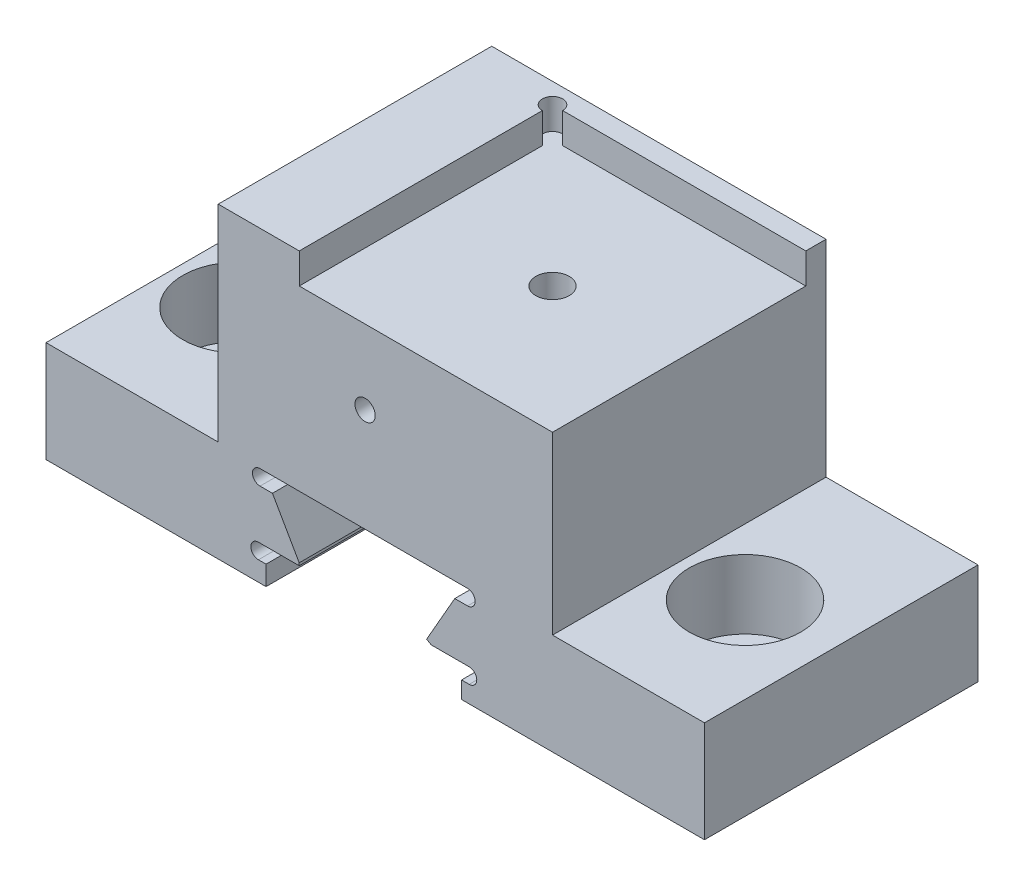
SolidWorks part; units mm, degrees
material "6061 合金"
ref_plane "前视基准面" through (0, 0, 0) normal (0, 0, 1) x (1, 0, 0)
ref_plane "上视基准面" through (0, 0, 0) normal (0, 1, 0) x (1, 0, 0)
ref_plane "右视基准面" through (0, 0, 0) normal (1, 0, 0) x (0, 0, -1)
sketch "草图1" plane through (0, 0, 0) normal (0, 1, 0) x (1, 0, 0)
  line L1 (-14.5, 14.5) -> (14.5, 14.5)
  line L2 (-14.5, 14.5) -> (-14.5, -14.5)
  line L3 (-14.5, -14.5) -> (14.5, -14.5)
  line L4 (14.5, 14.5) -> (14.5, -14.5)
  line L5 (-14.5, 14.5) -> (14.5, -14.5) construction
  line L6 (-14.5, -14.5) -> (14.5, 14.5) construction
  point P0 (0, 0)
  dimension "D1" = 29
  dimension "D2" = 29
extrude "凸台-拉伸1" add sketch "草图1" along normal blind 5
sketch "草图2" plane through (0, 5, 0) normal (0, -1, 0) x (1, 0, 0)
  line L1 (-12.5, 12.5) -> (12.5, 12.5)
  line L2 (-12.5, 12.5) -> (-12.5, -12.5)
  line L3 (-12.5, -12.5) -> (12.5, -12.5)
  line L4 (12.5, 12.5) -> (12.5, -12.5)
  line L5 (-12.5, 12.5) -> (12.5, -12.5) construction
  line L6 (-12.5, -12.5) -> (12.5, 12.5) construction
  point P0 (0, 0)
  dimension "D1" = 25
  dimension "D2" = 25
extrude "切除-拉伸1" cut sketch "草图2" along normal blind 3
sketch "草图3" plane through (0, 0, 0) normal (0, -1, 0) x (-1, 0, 0)
  line L1 (-14.5, -14.5) -> (20.5, -14.5)
  line L2 (-14.5, -14.5) -> (-14.5, 14.5)
  line L3 (-14.5, 14.5) -> (20.5, 14.5)
  line L4 (20.5, -14.5) -> (20.5, 14.5)
  dimension "D1" = 29
  dimension "D2" = 35
extrude "拉到底部滑块" add sketch "草图3" along normal up to surface (25.3412 mm away)
sketch "草图5" plane through (0, 2, 0) normal (0, 1, 0) x (1, 0, 0)
  circle A0 centre (0, 0) radius 2.1526
hole_wizard "M4 螺纹孔1" positions "3D草图1" profile "草图6" tap size "M4" standard "GB"
sketch3d "3D草图1"
  point P0 (0, 2, 0)
sketch "草图6" plane through (0, 2, 0) normal (1, 0, 0) x (0, 0, 1)
  line L0 (0, 0) -> (0, 11.0914)
  line L1 (0, 11.0914) -> (1.65, 10.1)
  line L2 (1.65, 10.1) -> (1.65, 0)
  line L5 (1.65, 0) -> (0, 0)
  line L10 (0, 11.0914) -> (-1.65, 10.1) construction
  line L11 (0, -6.35) -> (0, 107.95) construction
  dimension "螺纹孔钻头直径" = 3.3
  dimension "螺纹孔钻头深度" = 10.1
  dimension "导头角度" = 118
cosmetic thread "孔螺蚊线1" parameters "D1"=8, "D2"=4
sketch "草图9" plane through (0, 5, 0) normal (0, 1, 0) x (1, 0, 0)
  circle A0 centre (-12.5, 12.5) radius 1
extrude "切除-拉伸2" cut sketch "草图9" against normal up to surface (3 mm away) up to face at (0, 2, 1.65)
sketch "草图11" plane through (-14.5, 0, 0) normal (-1, 0, 0) x (0, 0, 1)
  line L4 (-14.5, 0) -> (14.5, 0)
  line L5 (14.5, 0) -> (14.5, 5)
  line L6 (14.5, 5) -> (-14.5, 5)
  line L7 (-14.5, 5) -> (-14.5, 0)
  line L8 (-14.5, 0) -> (14.5, 0)
  line L9 (14.5, 0) -> (14.5, 5)
  line L10 (14.5, 5) -> (-14.5, 5)
  line L11 (-14.5, 5) -> (-14.5, 0)
  dimension "D1" = 0
extrude "凸台-拉伸4" add sketch "草图11" along normal up to surface (6 mm away) up to face at (-20.5, -12.6706, 0)
sketch "草图17" plane through (0, 5, 0) normal (0, 1, 0) x (1, 0, 0)
  line L0 (-20.5, -14.5) -> (14.5, -14.5) construction
  line L1 (14.5, -14.5) -> (14.5, 14.5) construction
  line L2 (-20.5, -14.5) -> (14.5, -14.5)
  line L3 (14.5, -14.5) -> (14.5, 14.5)
  line L4 (-20.5, -12.5) -> (12.5, -12.5)
  line L5 (12.5, -12.5) -> (12.5, 14.5)
  line L6 (12.5, 14.5) -> (14.5, 14.5)
  line L7 (-20.5, -12.5) -> (-20.5, -14.5)
  dimension "D1" = 2
extrude "切除-拉伸8" cut sketch "草图17" against normal through all
sketch "草图18" plane through (0, -25.3412, 0) normal (0, -1, 0) x (1, 0, 0)
  line L0 (0, 0) -> (-6, 0) construction
  line L1 (16.5, 0) -> (-16.5, 0) construction
  line L2 (-6, 0) -> (-6, 12.5) construction
  line L3 (12.5, 12.5) -> (-20.5, 12.5) construction
  circle A0 centre (-6, 0) radius 1.512
  dimension "D1" = 6
sketch "草图19" plane through (0, -25.3412, 0) normal (0, -1, 0) x (-1, 0, 0)
  line L0 (-12.5, -12.5) -> (20.5, -12.5) construction
  line L1 (46, -12.5) -> (-34, -12.5)
  line L2 (46, -12.5) -> (46, 12.5)
  line L3 (46, 12.5) -> (-34, 12.5)
  line L4 (-34, -12.5) -> (-34, 12.5)
  line L5 (46, -12.5) -> (-34, 12.5) construction
  line L6 (46, 12.5) -> (-34, -12.5) construction
  point P0 (6, 0)
  dimension "D1" = 80
extrude "凸台-拉伸5" add sketch "草图19" against normal blind 10
sketch "草图21" plane through (0, -15.3412, 0) normal (0, 1, 0) x (1, 0, 0)
  line L0 (-6, 0) -> (-31, 0)
  line L3 (-16.5, 0) -> (16.5, 0) construction
  line L4 (-6, 0) -> (19, 0)
  dimension "D1" = 25
  dimension "D2" = 25
hole_wizard "打孔尺寸(%根据)内六角圆柱头螺钉的类型1" positions "3D草图2" profile "草图22" counterbore size "M6" standard "GB"
sketch3d "3D草图2"
  point P0 (-31, -15.3412, 0)
  point P3 (19, -15.3412, 0)
sketch "草图22" plane through (-31, -15.3412, 0) normal (1, 0, 0) x (0, 0, 1)
  line L0 (0, 0) -> (0, 12.0828)
  line L1 (0, 12.0828) -> (3.3, 10.1)
  line L2 (3.3, 10.1) -> (3.3, 6.8)
  line L3 (3.3, 6.8) -> (5.5, 6.8)
  line L4 (5.5, 6.8) -> (5.5, 0)
  line L5 (5.5, 0) -> (0, 0)
  line L10 (0, 12.0828) -> (-3.3, 10.1) construction
  line L11 (0, -6.35) -> (0, 107.95) construction
  dimension "孔直径" = 6.6
  dimension "孔深度" = 10.1
  dimension "柱形沉头孔直径" = 11
  dimension "柱形沉头孔深度" = 6.8
  dimension "导头角度" = 118
sketch "草图23" plane through (0, 0, -12.5) normal (0, 0, -1) x (-1, 0, 0)
  line L1 (-34, -15.3412) -> (46, -15.3412)
  line L2 (-34, -15.3412) -> (-34, -25.3412)
  line L3 (-34, -25.3412) -> (46, -25.3412)
  line L4 (46, -15.3412) -> (46, -25.3412)
extrude "凸台-拉伸6" add sketch "草图23" along normal up to surface (2 mm away) up to face at (-4, -10.1706, -14.5)
sketch "草图24" plane through (-46, 0, 0) normal (-1, 0, 0) x (0, 0, 1)
  line L4 (-14.5, -25.3412) -> (12.5, -25.3412)
  line L5 (12.5, -25.3412) -> (12.5, -15.3412)
  line L6 (12.5, -15.3412) -> (-14.5, -15.3412)
  line L7 (-14.5, -15.3412) -> (-14.5, -25.3412)
  line L8 (-14.5, -25.3412) -> (12.5, -25.3412)
  line L9 (12.5, -25.3412) -> (12.5, -15.3412)
  line L10 (12.5, -15.3412) -> (-14.5, -15.3412)
  line L11 (-14.5, -15.3412) -> (-14.5, -25.3412)
  dimension "D1" = 0
extrude "切除-拉伸9" cut sketch "草图24" against normal blind 2
sketch "草图25" plane through (0, -25.3412, 0) normal (0, -1, 0) x (1, 0, 0)
  line L0 (-31, 0) -> (-21, 0) construction
  line L1 (-6, 0) -> (-31, 0) construction
  line L2 (19, 0) -> (9, 0) construction
  line L3 (-6, 0) -> (19, 0) construction
  dimension "D1" = 10
hole_wizard "大小mm 暗销孔1" positions "3D草图3" profile "草图26" hole size "Ø4.0" standard "GB"
sketch3d "3D草图3"
  point P0 (-21, -25.3412, 0)
sketch "草图26" plane through (-21, -25.3412, 0) normal (1, 0, 0) x (0, 0, -1)
  line L0 (0, 0) -> (0, 6.2017)
  line L1 (0, 6.2017) -> (2, 5)
  line L2 (2, 5) -> (2, 0)
  line L5 (2, 0) -> (0, 0)
  line L10 (0, 6.2017) -> (-2, 5) construction
  line L11 (0, -6.35) -> (0, 107.95) construction
  dimension "孔直径" = 4
  dimension "孔深度" = 5
  dimension "导头角度" = 118
sketch "草图27" plane through (0, -25.3412, 0) normal (0, -1, 0) x (1, 0, 0)
  line L0 (8.5, 0) -> (9.5, 0) construction
  line L1 (8.5, 2) -> (9.5, 2)
  line L2 (8.5, -2) -> (9.5, -2)
  arc A0 (8.5, 2) -> (8.5, -2) centre (8.5, 0) ccw
  arc A1 (9.5, -2) -> (9.5, 2) centre (9.5, 0) ccw
  circle A2 centre (-21, 0) radius 2 construction
  point P2 (9, 0)
  dimension "D1" = 1
extrude "切除-拉伸10" cut sketch "草图27" against normal blind 5
sketch "草图28" plane through (0, 0, 12.5) normal (0, 0, 1) x (1, 0, 0)
  line L0 (-6, -25.3412) -> (-6, -5.3412) construction
  circle A0 centre (-6, -5.3412) radius 1
  dimension "D1" = 20
extrude "切除-拉伸11" cut sketch "草图28" against normal blind 2
hole_wizard "M6 螺纹孔1" positions "3D草图4" profile "草图29" tap size "M6" standard "GB"
sketch3d "3D草图4"
  point P0 (-6, -25.3412, 0)
sketch "草图29" plane through (-6, -25.3412, 0) normal (1, 0, 0) x (0, 0, -1)
  line L0 (0, 0) -> (0, 11.5022)
  line L1 (0, 11.5022) -> (2.5, 10)
  line L2 (2.5, 10) -> (2.5, 0)
  line L5 (2.5, 0) -> (0, 0)
  line L10 (0, 11.5022) -> (-2.5, 10) construction
  line L11 (0, -6.35) -> (0, 107.95) construction
  dimension "螺纹孔钻头直径" = 5
  dimension "螺纹孔钻头深度" = 10
  dimension "导头角度" = 118
cosmetic thread "孔螺蚊线2" parameters "D1"=10, "D2"=6
sketch "草图30" plane through (0, -25.3412, 0) normal (0, -1, 0) x (-1, 0, 0)
  circle A0 centre (21, 0) radius 2
  circle A1 centre (-9, 0) radius 2
extrude "切除-拉伸12" cut sketch "草图31" against normal through all and the other way through all
sketch "草图31" plane through (-6.0032, 14.6588, 10.4718) normal (0, 0, 1) x (1, 0, 0)
  line L13 (10.1171, -31.7) -> (8.8541, -31.7)
  line L14 (8.8541, -31.7) -> (6.0752, -36.5641)
  line L15 (6.0752, -36.5641) -> (6.5318, -36.825)
  line L16 (6.5318, -36.825) -> (10.275, -36.825)
  line L17 (10.275, -38.325) -> (9.525, -38.325)
  line L18 (9.525, -38.325) -> (9.525, -40)
  line L19 (-9.7761, -40) -> (-9.7761, -38.0744)
  line L20 (-9.7761, -38.0744) -> (-10.5261, -38.0744)
  line L21 (-10.5261, -36.5744) -> (-6.5013, -36.5744)
  line L22 (-6.5013, -36.5744) -> (-6.5013, -36.3244)
  line L23 (-6.5013, -36.3244) -> (-9.1432, -31.7)
  line L24 (-9.1432, -31.7) -> (-10.3692, -31.7)
  line L25 (-10.3692, -30.2) -> (10.1171, -30.2)
  line L26 (-9.7761, -40) -> (9.525, -40)
  arc A4 (10.1171, -31.7) -> (10.1171, -30.2) centre (10.1171, -30.95) ccw
  arc A5 (10.275, -38.325) -> (10.275, -36.825) centre (10.275, -37.575) ccw
  arc A6 (-10.5261, -36.5744) -> (-10.5261, -38.0744) centre (-10.5261, -37.3244) ccw
  arc A7 (-10.3692, -30.2) -> (-10.3692, -31.7) centre (-10.3692, -30.95) ccw
sketch "草图32" plane through (-44, 0, 0) normal (-1, 0, 0) x (0, 0, 1)
  line L4 (-14.5, -15.3412) -> (-14.5, -25.3412)
  line L5 (-14.5, -25.3412) -> (12.5, -25.3412)
  line L6 (12.5, -25.3412) -> (12.5, -15.3412)
  line L7 (12.5, -15.3412) -> (-14.5, -15.3412)
  line L8 (-14.5, -15.3412) -> (-14.5, -25.3412)
  line L9 (-14.5, -25.3412) -> (12.5, -25.3412)
  line L10 (12.5, -25.3412) -> (12.5, -15.3412)
  line L11 (12.5, -15.3412) -> (-14.5, -15.3412)
  dimension "D1" = 0
extrude "切除-拉伸13" cut sketch "草图32" against normal blind 6.5
sketch "草图33" plane through (34, 0, 0) normal (1, 0, 0) x (0, 0, -1)
  line L4 (-12.5, -25.3412) -> (14.5, -25.3412)
  line L5 (14.5, -25.3412) -> (14.5, -15.3412)
  line L6 (14.5, -15.3412) -> (-12.5, -15.3412)
  line L7 (-12.5, -15.3412) -> (-12.5, -25.3412)
  line L8 (-12.5, -25.3412) -> (14.5, -25.3412)
  line L9 (14.5, -25.3412) -> (14.5, -15.3412)
  line L10 (14.5, -15.3412) -> (-12.5, -15.3412)
  line L11 (-12.5, -15.3412) -> (-12.5, -25.3412)
  dimension "D1" = 0
extrude "切除-拉伸14" cut sketch "草图33" against normal blind 6.5
sketch "草图34" plane through (0, -25.3412, 0) normal (0, -1, 0) x (1, 0, 0)
  line L0 (-21, 0) -> (-21, -8) construction
  line L2 (9, -8) -> (9, 0) construction
  line L4 (-21, 0) -> (-21, 8) construction
  circle A0 centre (-21, -8) radius 2
  circle A1 centre (9, -8) radius 2
  circle A2 centre (-21, 8) radius 2
  point P9 (9, -4.1683)
  point P10 (9, -6.1891)
sketch "草图35" plane through (0, -25.3412, 0) normal (0, -1, 0) x (1, 0, 0)
  line L0 (8.5, -8) -> (9.5, -8) construction
  line L2 (8.5, -6) -> (9.5, -6)
  line L3 (8.5, -10) -> (9.5, -10)
  line L4 (9, -8) -> (9, 0) construction
  arc A0 (8.5, -6) -> (8.5, -10) centre (8.5, -8) ccw
  arc A1 (9.5, -10) -> (9.5, -6) centre (9.5, -8) ccw
  circle A2 centre (-21, 0) radius 2 construction
  point P5 (9, -8)
  point P12 (0, 0)
  dimension "D1" = 1
extrude "切除-拉伸15" cut sketch "草图35" against normal up to surface (5 mm away) up to face at (9, -20.3412, 0)
hole_wizard "大小mm 暗销孔2" positions "3D草图5" profile "草图36" hole size "Ø4.0" standard "GB"
sketch3d "3D草图5"
  point P0 (-21, -25.3412, -8)
sketch "草图36" plane through (-21, -25.3412, -8) normal (1, 0, 0) x (0, 0, -1)
  line L0 (0, 0) -> (0, 6.2017)
  line L1 (0, 6.2017) -> (2, 5)
  line L2 (2, 5) -> (2, 0)
  line L5 (2, 0) -> (0, 0)
  line L10 (0, 6.2017) -> (-2, 5) construction
  line L11 (0, -6.35) -> (0, 107.95) construction
  dimension "孔直径" = 4
  dimension "孔深度" = 5
  dimension "导头角度" = 118
hole_wizard "大小mm 暗销孔3" positions "3D草图6" profile "草图37" hole size "Ø4.0" standard "GB"
sketch3d "3D草图6"
  point P0 (-21, -25.3412, 8)
sketch "草图37" plane through (-21, -25.3412, 8) normal (1, 0, 0) x (0, 0, -1)
  line L0 (0, 0) -> (0, 6.2017)
  line L1 (0, 6.2017) -> (2, 5)
  line L2 (2, 5) -> (2, 0)
  line L5 (2, 0) -> (0, 0)
  line L10 (0, 6.2017) -> (-2, 5) construction
  line L11 (0, -6.35) -> (0, 107.95) construction
  dimension "孔直径" = 4
  dimension "孔深度" = 5
  dimension "导头角度" = 118
